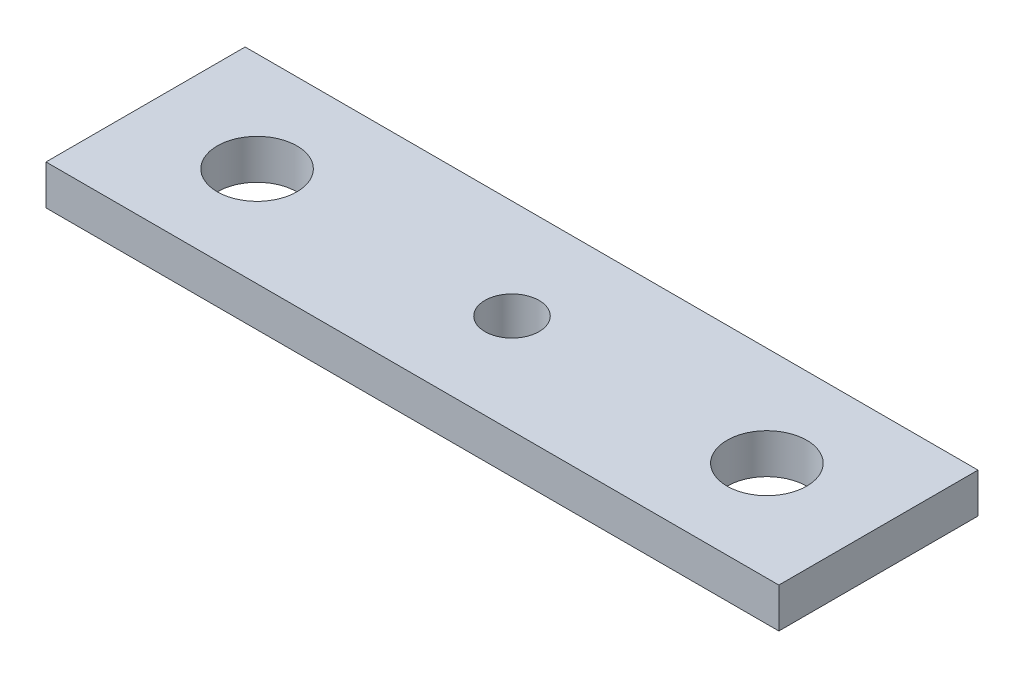
SolidWorks part; units mm, degrees
material "Q235锻制"
ref_plane "前视基准面" through (0, 0, 0) normal (0, 0, 1) x (1, 0, 0)
ref_plane "上视基准面" through (0, 0, 0) normal (0, 1, 0) x (1, 0, 0)
ref_plane "右视基准面" through (0, 0, 0) normal (1, 0, 0) x (0, 0, -1)
sketch "草图1" plane through (0, 0, 0) normal (0, 1, 0) x (1, 0, 0)
  line L1 (-46, -12.5) -> (46, -12.5)
  line L2 (-46, -12.5) -> (-46, 12.5)
  line L3 (-46, 12.5) -> (46, 12.5)
  line L4 (46, -12.5) -> (46, 12.5)
  line L5 (-46, -12.5) -> (46, 12.5) construction
  line L6 (-46, 12.5) -> (46, -12.5) construction
  point P0 (0, 0)
  dimension "D1" = 25
  dimension "D2" = 92
extrude "凸台-拉伸1" add sketch "草图1" along normal mid plane 5
sketch "草图2" plane through (0, 2.5, 0) normal (0, 1, 0) x (1, 0, 0)
  line L0 (-32, 0) -> (32, 0) construction
  line L2 (-2.75, 0) -> (2.75, 0) construction
  circle A0 centre (32, 0) radius 5
  circle A1 centre (-32, 0) radius 5
  point P4 (0, 0)
  dimension "D2" = 10
  dimension "D3" = 10
  dimension "D1" = 64
extrude "切除-拉伸1" cut sketch "草图2" against normal through all
hole_wizard "M8 螺纹孔1" positions "草图5" profile "草图4" tap size "M8" standard "GB" end condition through all
sketch "草图5" plane through (0, 2.5, 0) normal (0, 1, 0) x (1, 0, 0)
  point P0 (0, 0)
sketch "草图4" plane through (0, 2.5, 0) normal (1, 0, 0) x (0, 0, 1)
  line L0 (0, 0) -> (0, 5)
  line L1 (0, 5) -> (3.4, 5)
  line L2 (3.4, 5) -> (3.4, 0)
  line L5 (3.4, 0) -> (0, 0)
  line L11 (0, -6.35) -> (0, 107.95) construction
  dimension "通孔螺纹孔钻头直径" = 6.8
  dimension "通孔螺纹孔钻头深度" = 5
cosmetic thread "孔螺纹线1" parameters "D2"=8
